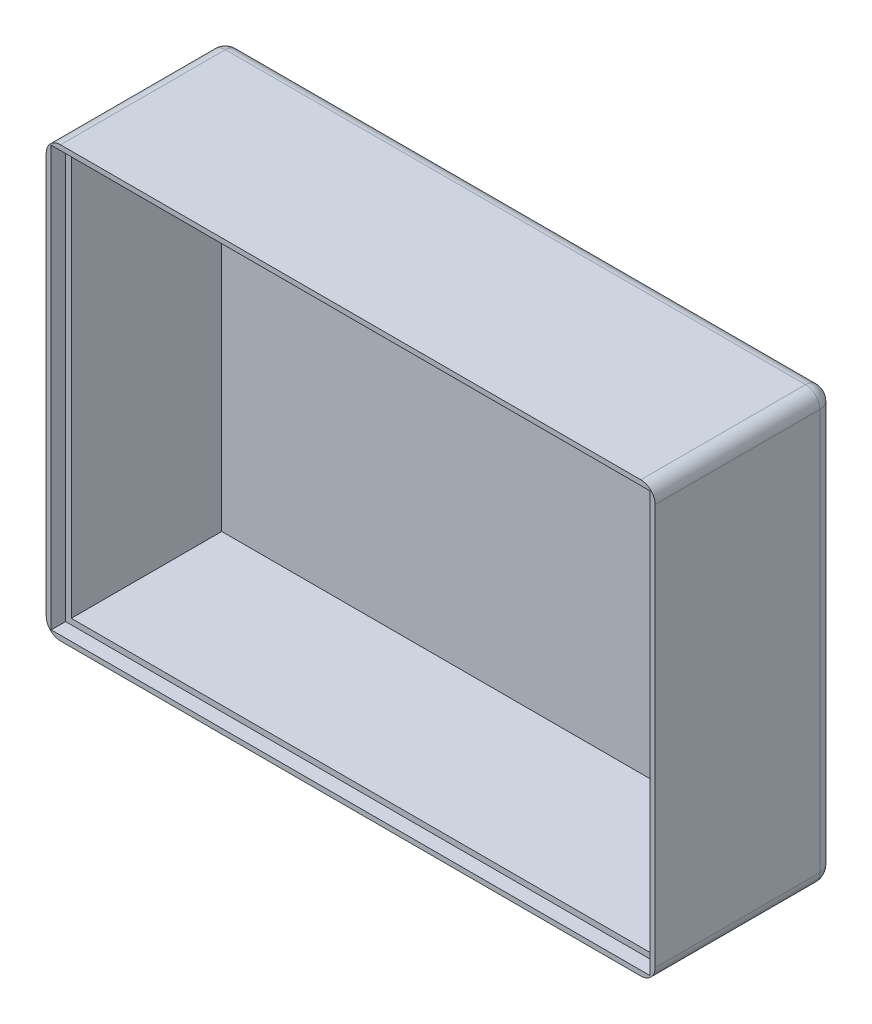
SolidWorks part; units mm, degrees
ref_plane "前视基准面" through (0, 0, 0) normal (0, 0, 1) x (1, 0, 0)
ref_plane "上视基准面" through (0, 0, 0) normal (0, 1, 0) x (1, 0, 0)
ref_plane "右视基准面" through (0, 0, 0) normal (1, 0, 0) x (0, 0, -1)
other "Configuration Table"
sketch "草图1" plane through (0, 0, 0) normal (0, 0, 1) x (1, 0, 0)
  line L1 (0, 0) -> (85, 0)
  line L2 (0, 0) -> (0, -60)
  line L3 (0, -60) -> (85, -60)
  line L4 (85, 0) -> (85, -60)
  dimension "D1" = 85
  dimension "D2" = 60
extrude "凸台-拉伸1" add sketch "草图1" along normal blind 25 contours L2 L3 L4 L1
sketch "草图2" plane through (0, 0, 25) normal (0, 0, 1) x (1, 0, 0)
  line L0 (0, -60) -> (85, -60) construction
  line L1 (1.5, -1.5) -> (83.5, -1.5)
  line L2 (1.5, -1.5) -> (1.5, -58.5)
  line L3 (1.5, -58.5) -> (83.5, -58.5)
  line L4 (83.5, -1.5) -> (83.5, -58.5)
  line L5 (0, 0) -> (0, -60) construction
  line L6 (0, 0) -> (85, 0) construction
  line L7 (85, 0) -> (85, -60) construction
  dimension "D1" = 1.5
  dimension "D2" = 1.5
  dimension "D3" = 1.5
  dimension "D4" = 1.5
extrude "切除-拉伸1" cut sketch "草图2" against normal blind 23
sketch "草图3" plane through (0, 0, 25) normal (0, 0, 1) x (1, 0, 0)
  line L0 (0, 0) -> (0, -60) construction
  line L1 (0.7, -0.7) -> (84.3, -0.7)
  line L2 (0.7, -0.7) -> (0.7, -59.3)
  line L3 (0.7, -59.3) -> (84.3, -59.3)
  line L4 (84.3, -0.7) -> (84.3, -59.3)
  line L5 (0, -60) -> (85, -60) construction
  line L6 (85, 0) -> (85, -60) construction
  line L7 (0, 0) -> (85, 0) construction
  dimension "D1" = 0.7
  dimension "D2" = 0.7
  dimension "D3" = 0.7
  dimension "D4" = 0.7
extrude "切除-拉伸2" cut sketch "草图3" against normal blind 2
fillet "圆角1" radius 2 8 edges at (42.5, -60, 0) (85, -60, 12.5) (0, -60, 12.5) (0, -30, 0) (0, 0, 12.5) (42.5, 0, 0) (85, 0, 12.5) (85, -30, 0)
